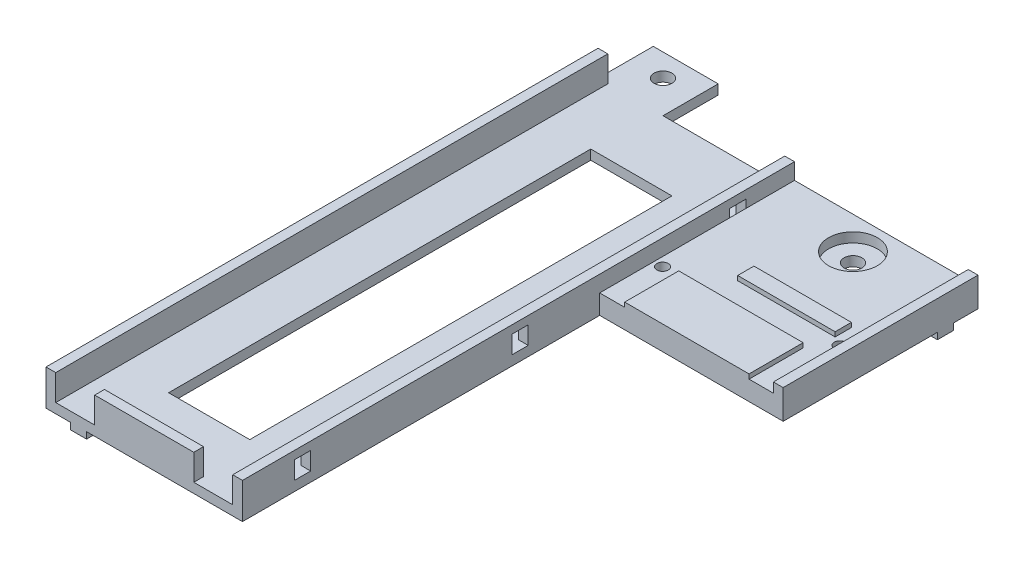
SolidWorks part; units mm, degrees
ref_plane "Front Plane" through (0, 0, 0) normal (0, 0, 1) x (1, 0, 0)
ref_plane "Top Plane" through (0, 0, 0) normal (0, 1, 0) x (1, 0, 0)
ref_plane "Right Plane" through (0, 0, 0) normal (1, 0, 0) x (0, 0, -1)
sketch "Sketch1" plane through (0, 0, 0) normal (0, 1, 0) x (1, 0, 0)
  line L1 (-30.25, 85) -> (30.25, 85)
  line L2 (-30.25, 85) -> (-30.25, -85)
  line L3 (-30.25, -85) -> (30.25, -85)
  line L4 (30.25, 85) -> (30.25, -85)
  line L5 (-30.25, 85) -> (30.25, -85) construction
  line L6 (-30.25, -85) -> (30.25, 85) construction
  point P0 (0, 0)
  dimension "D1" = 60.5
  dimension "D2" = 170
extrude "Boss-Extrude1" add sketch "Sketch1" along normal blind 11
sketch "Sketch2" plane through (0, 11, 0) normal (0, 1, 0) x (1, 0, 0)
  line L0 (30.25, 85) -> (-30.25, 85) construction
  line L1 (-27.25, -82) -> (27.25, -82)
  line L2 (-27.25, -82) -> (-27.25, 85)
  line L3 (-27.25, 85) -> (27.25, 85)
  line L4 (27.25, -82) -> (27.25, 85)
  line L5 (-27.25, -82) -> (27.25, 85) construction
  line L6 (-27.25, 85) -> (27.25, -82) construction
  line L7 (-30.25, -85) -> (30.25, -85) construction
  point P0 (0, 1.5)
  dimension "D1" = 54.5
  dimension "D2" = 0
  dimension "D3" = 3
extrude "Cut-Extrude1" cut sketch "Sketch2" against normal blind 8
sketch "Sketch3" plane through (0, 11, 0) normal (0, 1, 0) x (1, 0, 0)
  line L0 (-30.25, -85) -> (30.25, -85) construction
  line L1 (-27.25, -82) -> (-15.25, -82)
  line L2 (-27.25, -82) -> (-27.25, -85)
  line L3 (-27.25, -85) -> (-15.25, -85)
  line L4 (-15.25, -82) -> (-15.25, -85)
  line L6 (27.25, -82) -> (15.25, -82)
  line L7 (27.25, -82) -> (27.25, -85)
  line L8 (27.25, -85) -> (15.25, -85)
  line L9 (15.25, -82) -> (15.25, -85)
  dimension "D1" = 12
  dimension "D2" = 12
extrude "Cut-Extrude2" cut sketch "Sketch3" against normal blind 8
sketch "Sketch4" plane through (0, 0, 0) normal (0, -1, 0) x (1, 0, 0)
  line L1 (-30.25, -85) -> (-10.25, -85)
  line L2 (-30.25, -85) -> (-30.25, -105)
  line L3 (-30.25, -105) -> (-10.25, -105)
  line L4 (-10.25, -85) -> (-10.25, -105)
  circle A0 centre (-20.25, -95) radius 2.75
  dimension "D4" = 5.5
  dimension "D1" = 20
  dimension "D2" = 20
  dimension "D3" = 10
  dimension "D5" = 10
extrude "Boss-Extrude3" add sketch "Sketch4" against normal blind 3
sketch "Sketch5" plane through (27.25, 0, 0) normal (-1, 0, 0) x (0, 0, 1)
  line L0 (85, 3) -> (-85, 3) construction
  line L1 (69, 3) -> (64, 3)
  line L2 (69, 3) -> (69, 8.5)
  line L3 (69, 8.5) -> (64, 8.5)
  line L4 (64, 3) -> (64, 8.5)
  line L5 (85, 3) -> (85, 11) construction
  line L6 (-3, 3) -> (2, 3)
  line L7 (-3, 3) -> (-3, 8.5)
  line L8 (-3, 8.5) -> (2, 8.5)
  line L9 (2, 3) -> (2, 8.5)
  line L10 (-65, 3) -> (-70, 3)
  line L11 (-65, 3) -> (-65, 8.5)
  line L12 (-65, 8.5) -> (-70, 8.5)
  line L13 (-70, 3) -> (-70, 8.5)
  dimension "D1" = 16
  dimension "D2" = 5
  dimension "D3" = 5.5
  dimension "D4" = 83
  dimension "D5" = 5
  dimension "D6" = 5.5
  dimension "D7" = 5
  dimension "D8" = 5.5
  dimension "D9" = 150
extrude "Cut-Extrude3" cut sketch "Sketch5" against normal blind 16
sketch "Sketch7" plane through (0, 0, 0) normal (0, -1, 0) x (1, 0, 0)
  line L1 (30.25, -85) -> (86.75, -85)
  line L2 (30.25, -85) -> (30.25, -25)
  line L3 (30.25, -25) -> (86.75, -25)
  line L4 (86.75, -85) -> (86.75, -25)
  circle A0 centre (81.25, -48) radius 1.75
  circle A2 centre (32.95, -41.65) radius 1.75
  dimension "D3" = 3.5
  dimension "D9" = 3.5
  dimension "D1" = 56.5
  dimension "D2" = 60
  dimension "D5" = 5.5
  dimension "D8" = 45
  dimension "D10" = 48.3
  dimension "D11" = 6.35
extrude "Boss-Extrude7" add sketch "Sketch7" against normal blind 3
sketch "Sketch9" plane through (0, 3, 0) normal (0, 1, 0) x (1, 0, 0)
  line L0 (86.75, 25) -> (30.25, 25) construction
  line L1 (37.95, 25) -> (76.25, 25)
  line L2 (37.95, 25) -> (37.95, 41.65)
  line L3 (37.95, 41.65) -> (76.25, 41.65)
  line L4 (76.25, 25) -> (76.25, 41.65)
  line L6 (78.25, 49.5) -> (48.25, 49.5)
  line L7 (78.25, 49.5) -> (78.25, 54.5)
  line L8 (78.25, 54.5) -> (48.25, 54.5)
  line L9 (48.25, 49.5) -> (48.25, 54.5)
  circle A0 centre (32.95, 41.65) radius 1.75 construction
  circle A1 centre (81.25, 48) radius 1.75 construction
  circle A2 centre (81.25, 48) radius 1.75 construction
  dimension "D1" = 0
  dimension "D2" = 5
  dimension "D3" = 5
  dimension "D4" = 1.5
  dimension "D5" = 5
  dimension "D6" = 3
  dimension "D7" = 30
extrude "Boss-Extrude8" add sketch "Sketch9" along normal blind 1.4
sketch "Sketch10" plane through (0, 3, 0) normal (0, 1, 0) x (1, 0, 0)
  line L0 (30.25, 85) -> (86.75, 85) construction
  line L1 (86.75, 25) -> (83.75, 25)
  line L2 (86.75, 25) -> (86.75, 85)
  line L3 (86.75, 85) -> (83.75, 85)
  line L4 (83.75, 25) -> (83.75, 85)
  dimension "D1" = 3
extrude "Boss-Extrude9" add sketch "Sketch10" along normal blind 6
sketch "Sketch12" plane through (0, 3, 0) normal (0, 1, 0) x (1, 0, 0)
  line L0 (30.25, 85) -> (83.75, 85) construction
  circle A0 centre (58.25, 75) radius 2.75
  dimension "D1" = 5.5
  dimension "D2" = 10
  dimension "D3" = 28
extrude "Cut-Extrude4" cut sketch "Sketch12" against normal blind 3
sketch "Sketch13" plane through (0, 0, 0) normal (0, -1, 0) x (1, 0, 0)
  line L0 (86.75, -85) -> (86.75, -25) construction
  line L1 (86.75, -77.5) -> (66.25, -77.5)
  line L2 (86.75, -77.5) -> (86.75, -72.5)
  line L3 (86.75, -72.5) -> (66.25, -72.5)
  line L4 (66.25, -77.5) -> (66.25, -72.5)
  line L5 (-30.25, 85) -> (30.25, 85) construction
  line L6 (50.25, -77.5) -> (20.25, -77.5)
  line L7 (50.25, -77.5) -> (50.25, -72.5)
  line L8 (50.25, -72.5) -> (20.25, -72.5)
  line L9 (20.25, -77.5) -> (20.25, -72.5)
  line L10 (-17.75, 85) -> (-22.75, 85)
  line L11 (-17.75, 85) -> (-17.75, -87)
  line L12 (-17.75, -87) -> (-22.75, -87)
  line L13 (-22.75, 85) -> (-22.75, -87)
  line L15 (-30.25, -105) -> (-30.25, 85) construction
  line L16 (86.75, -85) -> (-10.25, -85) construction
  circle A0 centre (-20.25, -95) radius 2.75 construction
  circle A1 centre (58.25, -75) radius 2.75 construction
  point P24 (50.25, -75)
  dimension "D8" = 8
  dimension "D1" = 8
  dimension "D2" = 7.5
  dimension "D3" = 5
  dimension "D4" = 5
  dimension "D5" = 5
  dimension "D6" = 7.5
  dimension "D7" = 7.5
  dimension "D9" = 8
  dimension "D10" = 30
extrude "Boss-Extrude10" add sketch "Sketch13" along normal blind 2
sketch "Sketch14" plane through (0, 4.4, 0) normal (0, 1, 0) x (1, 0, 0)
  line L0 (37.95, 41.65) -> (37.95, 25) construction
  line L1 (37.95, 25) -> (76.25, 25) construction
  line L2 (76.25, 25) -> (76.25, 41.65) construction
  line L3 (76.25, 41.65) -> (37.95, 41.65) construction
  line L4 (78.25, 49.5) -> (78.25, 54.5) construction
  line L5 (78.25, 54.5) -> (48.25, 54.5) construction
  line L6 (48.25, 54.5) -> (48.25, 49.5) construction
  line L7 (48.25, 49.5) -> (78.25, 49.5) construction
  line L8 (37.95, 41.65) -> (37.95, 25)
  line L9 (37.95, 25) -> (76.25, 25)
  line L10 (76.25, 25) -> (76.25, 41.65)
  line L11 (76.25, 41.65) -> (37.95, 41.65)
  line L12 (78.25, 49.5) -> (78.25, 54.5)
  line L13 (78.25, 54.5) -> (48.25, 54.5)
  line L14 (48.25, 54.5) -> (48.25, 49.5)
  line L15 (48.25, 49.5) -> (78.25, 49.5)
extrude "Boss-Extrude11" add sketch "Sketch14" along normal blind 3
sketch "Sketch15" plane through (0, 3, 0) normal (0, 1, 0) x (1, 0, 0)
  line L1 (30.25, 85) -> (83.75, 85)
  line L2 (30.25, 85) -> (30.25, 25)
  line L3 (30.25, 25) -> (83.75, 25)
  line L4 (83.75, 85) -> (83.75, 25)
  circle A0 centre (32.95, 41.65) radius 1.75 construction
  circle A1 centre (81.25, 48) radius 1.75 construction
  circle A2 centre (58.25, 75) radius 2.75 construction
  circle A3 centre (32.95, 41.65) radius 1.75
  circle A4 centre (81.25, 48) radius 1.75
  circle A5 centre (58.25, 75) radius 2.75
extrude "Boss-Extrude12" add sketch "Sketch15" along normal blind 3
sketch "Sketch16" plane through (0, 0, 0) normal (0, -1, 0) x (1, 0, 0)
  line L1 (81.25, -44.8246) -> (78.5, -46.4123)
  line L2 (78.5, -46.4123) -> (78.5, -49.5877)
  line L3 (78.5, -49.5877) -> (81.25, -51.1754)
  line L4 (81.25, -51.1754) -> (84, -49.5877)
  line L5 (84, -49.5877) -> (84, -46.4123)
  line L6 (84, -46.4123) -> (81.25, -44.8246)
  line L7 (32.95, -38.4746) -> (30.2, -40.0623)
  line L8 (30.2, -40.0623) -> (30.2, -43.2377)
  line L9 (30.2, -43.2377) -> (32.95, -44.8254)
  line L10 (32.95, -44.8254) -> (35.7, -43.2377)
  line L11 (35.7, -43.2377) -> (35.7, -40.0623)
  line L12 (35.7, -40.0623) -> (32.95, -38.4746)
  circle A0 centre (32.95, -41.65) radius 1.75 construction
  circle A1 centre (81.25, -48) radius 1.75 construction
  circle A2 centre (32.95, -41.65) radius 1.75
  circle A3 centre (81.25, -48) radius 1.75
  circle A4 centre (81.25, -48) radius 2.75 construction
  circle A5 centre (32.95, -41.65) radius 2.75 construction
  dimension "D1" = 5.5
  dimension "D2" = 5.5
extrude "Cut-Extrude5" cut sketch "Sketch16" against normal blind 3
sketch "Sketch17" plane through (0, 6, 0) normal (0, 1, 0) x (1, 0, 0)
  circle A0 centre (58.25, 75) radius 2.75 construction
  circle A1 centre (58.25, 75) radius 2.75
  circle A2 centre (58.25, 75) radius 7.5
  dimension "D1" = 15
extrude "Cut-Extrude6" cut sketch "Sketch17" against normal blind 3
sketch "Sketch18" plane through (0, 0, -105) normal (0, 0, -1) x (-1, 0, 0)
  line L4 (10.25, 0) -> (30.25, 0)
  line L5 (30.25, 0) -> (30.25, 3)
  line L6 (30.25, 3) -> (10.25, 3)
  line L7 (10.25, 3) -> (10.25, 0)
  line L8 (10.25, 0) -> (30.25, 0)
  line L9 (30.25, 0) -> (30.25, 3)
  line L10 (30.25, 3) -> (10.25, 3)
  line L11 (10.25, 3) -> (10.25, 0)
  dimension "D1" = 0
extrude "Cut-Extrude7" cut sketch "Sketch18" against normal blind 3
sketch "Sketch19" plane through (0, 3, 0) normal (0, 1, 0) x (1, 0, 0)
  line L0 (15.25, -85) -> (27.25, -85) construction
  line L1 (-12.5, -65) -> (12.5, -65)
  line L2 (-12.5, -65) -> (-12.5, 65)
  line L3 (-12.5, 65) -> (12.5, 65)
  line L4 (12.5, -65) -> (12.5, 65)
  line L5 (-12.5, -65) -> (12.5, 65) construction
  line L6 (-12.5, 65) -> (12.5, -65) construction
  point P0 (0, 0)
  dimension "D1" = 130
  dimension "D2" = 20
  dimension "D3" = 25
  dimension "D4" = 0
extrude "Cut-Extrude8" cut sketch "Sketch19" against normal through all both and the other way through all
